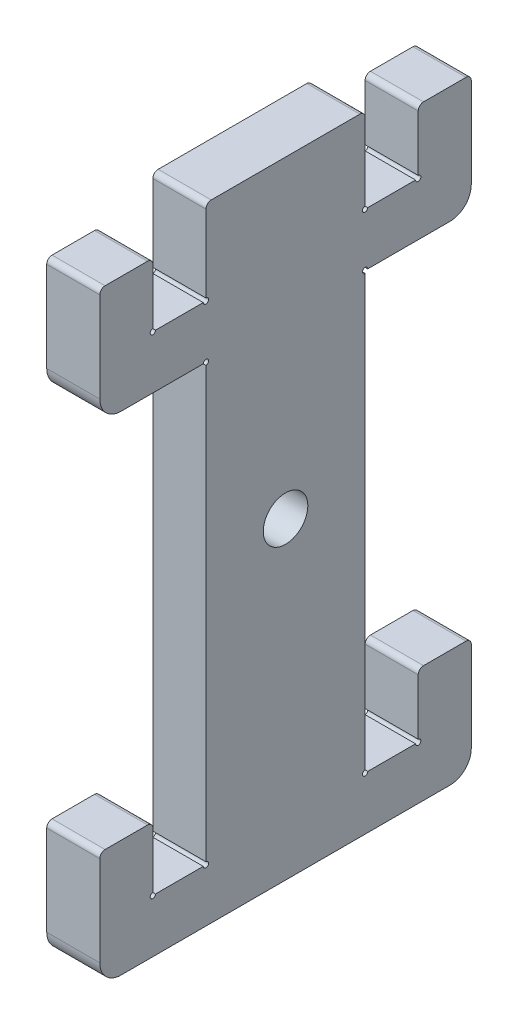
SolidWorks part; units mm, degrees
ref_plane "Plan de face" through (0, 0, 0) normal (0, 0, 1) x (1, 0, 0)
ref_plane "Plan de dessus" through (0, 0, 0) normal (0, 1, 0) x (1, 0, 0)
ref_plane "Plan de droite" through (0, 0, 0) normal (1, 0, 0) x (0, 0, -1)
sketch "Esquisse2" plane through (0, 0, 0) normal (1, 0, 0) x (0, 0, -1)
  line L0 (7.7509, -22.5453) -> (12.2498, -22.5453)
  line L1 (-7.5, 18.2043) -> (-7.5, -22.2952)
  line L2 (-6.9995, 31.4548) -> (6.9998, 31.4548)
  line L3 (-1.7207, 1.9547) -> (1.7207, 1.9547) construction
  line L4 (12.5, -17.0452) -> (12.5, -22.2953)
  line L5 (17.0001, -16.5452) -> (13.0003, -16.5452)
  line L6 (17.5, -17.0456) -> (17.5, -25.5452)
  line L7 (0, 1.9547) -> (0, -31.4548) construction
  line L8 (-15.5, -27.5452) -> (15.5, -27.5452)
  line L9 (15.5005, 18.4547) -> (7.7504, 18.4547)
  line L10 (7.5, 30.9552) -> (7.5, 23.7048)
  line L11 (12.2502, 23.4553) -> (7.7498, 23.4553)
  line L12 (12.5, 28.9557) -> (12.5, 23.7057)
  line L13 (17.5, 20.4547) -> (17.5, 28.9553)
  line L14 (17.0005, 29.4553) -> (13.0005, 29.4553)
  line L15 (7.5, -22.2952) -> (7.5, 18.2043)
  line L16 (-16.9996, 29.4548) -> (-12.9996, 29.4548)
  line L17 (-17.5, 20.4547) -> (-17.5, 28.9548)
  line L18 (-12.5, 28.9552) -> (-12.5, 23.7052)
  line L19 (-12.2498, 23.4548) -> (-7.7496, 23.4548)
  line L20 (-7.5, 30.9552) -> (-7.5, 23.7048)
  line L21 (-15.5, 18.4547) -> (-7.75, 18.4547)
  line L22 (-17.5, -17.0454) -> (-17.5, -25.5452)
  line L23 (-16.9998, -16.5452) -> (-13, -16.5452)
  line L24 (-12.5, -17.0452) -> (-12.5, -22.2952)
  line L25 (-7.7504, -22.5452) -> (-12.25, -22.5452)
  arc A0 (-12.9996, 29.4548) -> (-12.5, 28.9552) centre (-13, 28.9548) cw
  arc A1 (-16.9996, 29.4548) -> (-17.5, 28.9548) centre (-17, 28.9548) ccw
  arc A2 (-6.9995, 31.4548) -> (-7.5, 30.9552) centre (-7, 30.9548) ccw
  circle A3 centre (0, 1.9547) radius 2.1
  arc A4 (7.7498, 23.4553) -> (7.5, 23.7048) centre (7.4998, 23.4548) cw
  arc A5 (12.5, 23.7057) -> (12.2502, 23.4553) centre (12.5002, 23.4557) cw
  arc A6 (7.5, 18.2043) -> (7.7504, 18.4547) centre (7.5004, 18.4543) cw
  arc A7 (-17.5, 20.4547) -> (-15.5, 18.4547) centre (-15.5, 20.4547) ccw
  arc A8 (-17.5, -17.0454) -> (-16.9998, -16.5452) centre (-16.9998, -17.0454) cw
  arc A9 (-13, -16.5452) -> (-12.5, -17.0452) centre (-13, -17.0452) cw
  arc A10 (-17.5, -25.5452) -> (-15.5, -27.5452) centre (-15.5, -25.5452) ccw
  arc A11 (7.7509, -22.5453) -> (7.5, -22.2952) centre (7.5009, -22.5452) cw
  arc A12 (12.5, -22.2953) -> (12.2498, -22.5453) centre (12.4998, -22.5453) cw
  arc A13 (17.5, -25.5452) -> (15.5, -27.5452) centre (15.5004, -25.5456) cw
  arc A14 (-12.5, -22.2952) -> (-12.25, -22.5452) centre (-12.5, -22.5452) ccw
  arc A15 (-7.7504, -22.5452) -> (-7.5, -22.2952) centre (-7.5004, -22.5452) ccw
  arc A16 (-7.5, 18.2043) -> (-7.75, 18.4547) centre (-7.4996, 18.4547) ccw
  arc A17 (-12.5, 23.7052) -> (-12.2498, 23.4548) centre (-12.4998, 23.4552) ccw
  arc A18 (-7.7496, 23.4548) -> (-7.5, 23.7048) centre (-7.4996, 23.4548) ccw
  arc A19 (13.0003, -16.5452) -> (12.5, -17.0452) centre (13, -17.0452) ccw
  arc A20 (17.5, -17.0456) -> (17.0001, -16.5452) centre (17, -17.0452) ccw
  arc A21 (17.5, 20.4547) -> (15.5005, 18.4547) centre (15.5, 20.4547) cw
  arc A22 (6.9998, 31.4548) -> (7.5, 30.9552) centre (7, 30.9548) cw
  arc A23 (17.0005, 29.4553) -> (17.5, 28.9553) centre (17, 28.9553) cw
  arc A24 (13.0005, 29.4553) -> (12.5, 28.9557) centre (13, 28.9553) ccw
  point P16 (0.0002, 31.4548)
  point P67 (0, -27.5452)
  dimension "D2" = 0.5
  dimension "D3" = 0.5
  dimension "D6" = 4.2
  dimension "D8" = 0.25
  dimension "D9" = 0.25
  dimension "D13" = 2
  dimension "D14" = 2
  dimension "D30" = 2
  dimension "D31" = 1.9996
  dimension "D34" = 0.5
  dimension "D35" = 0.5
  dimension "D1" = 6
  dimension "D4" = 6
  dimension "D5" = 16.5
  dimension "D7" = 5
  dimension "D10" = 59
  dimension "D11" = 2
  dimension "D12" = 5
  dimension "D15" = 5
  dimension "D16" = 24.5
  dimension "D17" = 15
  dimension "D18" = 41
  dimension "D19" = 5
  dimension "D20" = 46
  dimension "D21" = 40.0005
  dimension "D22" = 6
  dimension "D23" = 5.0007
  dimension "D24" = 11
  dimension "D25" = 7.5
  dimension "D26" = 5
  dimension "D27" = 5
  dimension "D28" = 5
  dimension "D29" = 5
  dimension "D32" = 5
  dimension "D33" = 15
extrude "Boss.-Extru.2" add sketch "Esquisse2" along normal blind 5 separate body
